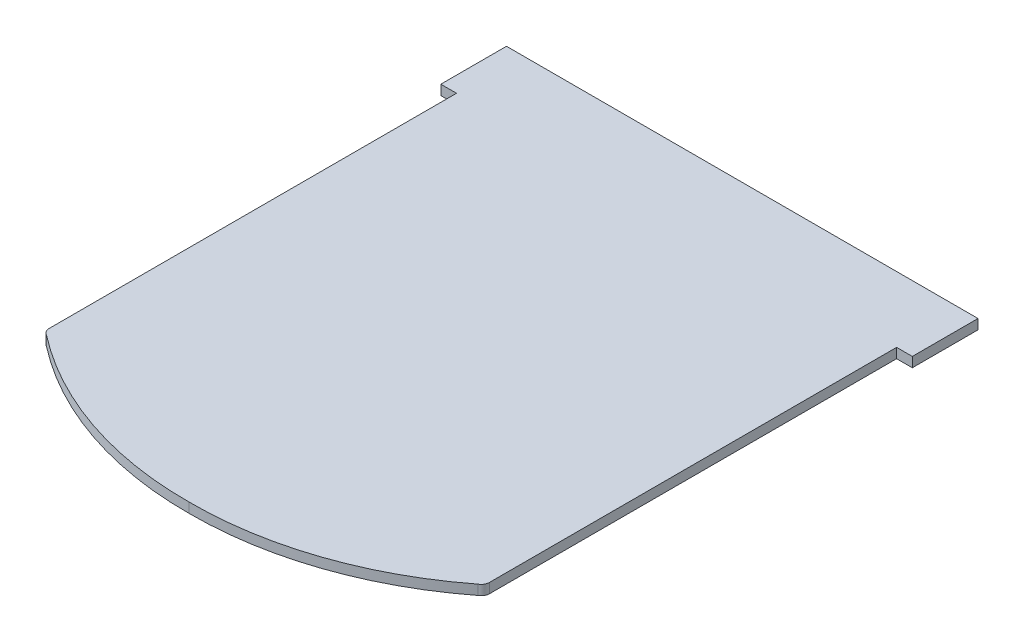
SolidWorks part; units mm, degrees
material "ASTM A240-T316"
ref_plane "Front Plane" through (0, 0, 0) normal (0, 0, 1) x (1, 0, 0)
ref_plane "Top Plane" through (0, 0, 0) normal (0, 1, 0) x (1, 0, 0)
ref_plane "Right Plane" through (0, 0, 0) normal (1, 0, 0) x (0, 0, -1)
sketch "Sketch1" plane through (0, 0, 0) normal (0, 1, 0) x (1, 0, 0)
  line L0 (0, -215.9) -> (0, -306.3875) construction
  line L2 (-212.725, -228.6) -> (-212.725, 165.1)
  line L3 (-212.725, 228.6) -> (212.725, 228.6)
  line L4 (212.725, -228.6) -> (212.725, 165.1)
  line L5 (-212.725, -228.6) -> (212.725, 228.6) construction
  line L6 (-212.725, 228.6) -> (212.725, -228.6) construction
  line L7 (212.725, 165.1) -> (227.9015, 165.1)
  line L8 (-212.725, 228.6) -> (-227.9015, 228.6)
  line L10 (-212.725, 165.1) -> (-227.9015, 165.1)
  line L11 (-227.9015, 228.6) -> (-227.9015, 165.1)
  line L12 (212.725, 228.6) -> (227.9015, 228.6)
  line L13 (227.9015, 228.6) -> (227.9015, 165.1)
  arc A7 (-212.725, -228.6) -> (-208.5731, -235.4275) centre (-204.8319, -228.4762) ccw
  arc A8 (0, -306.3875) -> (-208.5731, -235.4275) centre (-1.9096, 30.0094) cw
  arc A9 (212.725, -228.6) -> (208.5731, -235.4275) centre (204.8319, -228.4762) cw
  arc A10 (0, -306.3875) -> (208.5731, -235.4275) centre (1.9096, 30.0094) ccw
  point P0 (0, 0)
  point P14 (-220.3133, 165.1)
  point P21 (220.3132, 165.1)
  dimension "D1" = 425.45
  dimension "D2" = 457.2
  dimension "D3" = 77.7875
  dimension "D4" = 63.5
  dimension "D5" = 15.1765
extrude "Boss-Extrude3" add sketch "Sketch1" along normal blind 9.525
